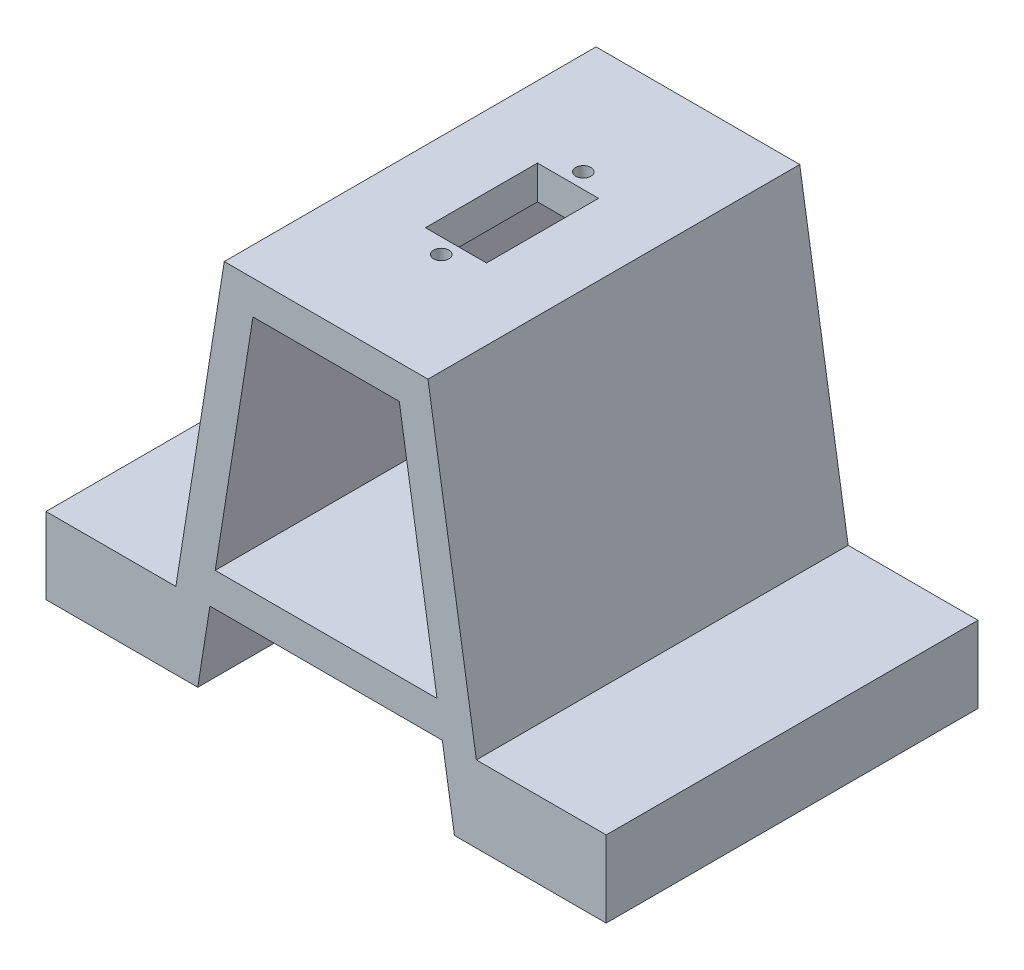
SolidWorks part; units mm, degrees
ref_plane "Front Plane" through (0, 0, 0) normal (0, 0, 1) x (1, 0, 0)
ref_plane "Top Plane" through (0, 0, 0) normal (0, 1, 0) x (1, 0, 0)
ref_plane "Right Plane" through (0, 0, 0) normal (1, 0, 0) x (0, 0, -1)
sketch "Sketch1" plane through (0, 0, 0) normal (0, 0, 1) x (1, 0, 0)
  line L0 (-55, 0) -> (55, 0)
  line L1 (55, 0) -> (55, 15)
  line L2 (55, 15) -> (29.5031, 15)
  line L3 (29.5031, 15) -> (20, 75)
  line L4 (20, 75) -> (-20, 75)
  line L5 (-20, 75) -> (-29.5031, 15)
  line L6 (-29.5031, 15) -> (-55, 15)
  line L7 (-55, 15) -> (-55, 0)
  line L8 (0, 0) -> (0, 75) construction
  dimension "D1" = 110
  dimension "D2" = 15
  dimension "D3" = 60
  dimension "D4" = 40
  dimension "D5" = 99
extrude "Boss-Extrude1" add sketch "Sketch1" along normal mid plane 73
sketch "Sketch2" plane through (0, 0, 36.5) normal (0, 0, 1) x (1, 0, 0)
  line L0 (-22.8208, 15) -> (22.8208, 15)
  line L1 (-21.7755, 21.6) -> (21.7755, 21.6)
  line L3 (-22.8208, 15) -> (-25.1966, 0)
  line L4 (21.7755, 21.6) -> (14.3631, 68.4)
  line L12 (-25.1966, 0) -> (25.1966, 0)
  line L15 (22.9843, 13.9675) -> (14.3631, 68.4)
  line L16 (14.3631, 68.4) -> (-14.3631, 68.4)
  line L17 (-14.3631, 68.4) -> (-22.9843, 13.9675)
  line L18 (25.1966, 0) -> (22.8208, 15)
  line L19 (14.3631, 68.4) -> (-14.3631, 68.4)
  line L20 (-14.3631, 68.4) -> (-21.7755, 21.6)
  dimension "D2" = 15
  dimension "D3" = 6.6
  dimension "D1" = 6.6
extrude "Cut-Extrude1" cut sketch "Sketch2" against normal through all
sketch "Sketch3" plane through (0, 75, 0) normal (0, 1, 0) x (1, 0, 0)
  line L1 (6, -11) -> (-6, -11)
  line L2 (6, -11) -> (6, 11)
  line L3 (6, 11) -> (-6, 11)
  line L4 (-6, -11) -> (-6, 11)
  line L5 (6, -11) -> (-6, 11) construction
  line L6 (6, 11) -> (-6, -11) construction
  point P0 (0, 0)
  dimension "D1" = 22
  dimension "D2" = 12
sketch "Sketch5" plane through (0, 75, 0) normal (0, 1, 0) x (1, 0, 0)
extrude "Cut-Extrude4" cut sketch "Sketch3" against normal blind 7
sketch "Sketch7" plane through (0, 75, 0) normal (0, 1, 0) x (1, 0, 0)
  circle A0 centre (0, 14) radius 1.5
  circle A1 centre (0.1022, -13.9996) radius 1.5
  point P4 (0, 0)
  point P6 (0, 0)
  dimension "D1" = 14
  dimension "D2" = 14
extrude "Cut-Extrude10" cut sketch "Sketch7" against normal blind 8
